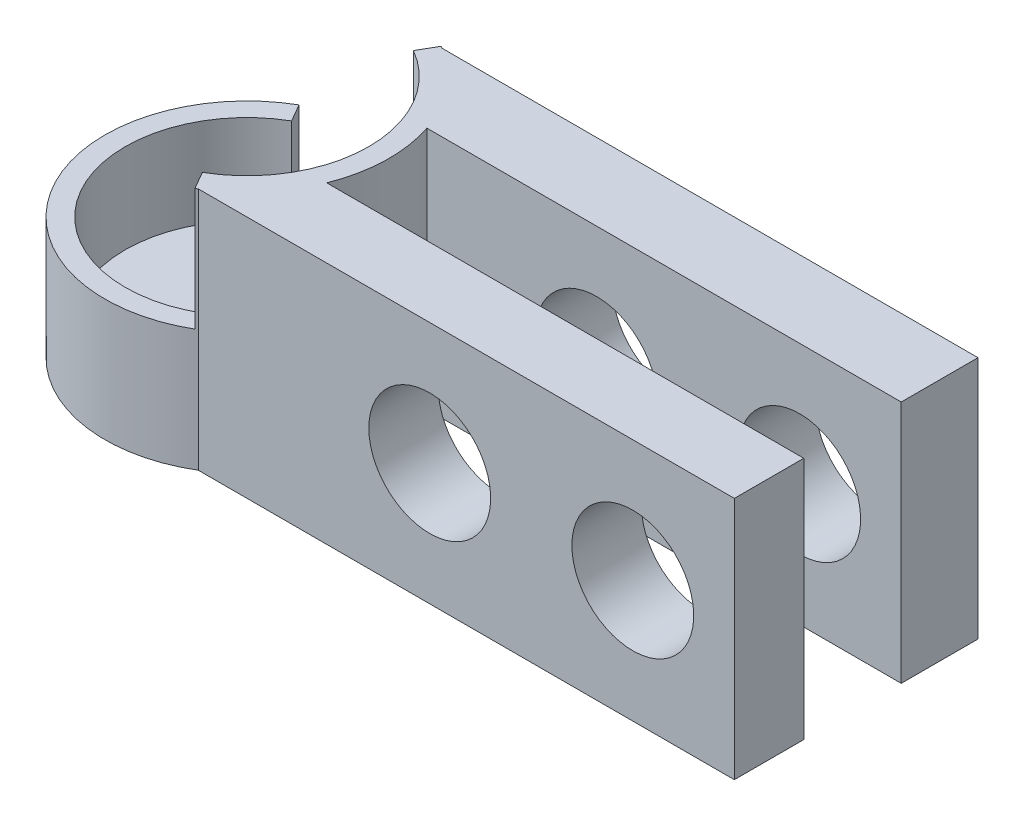
SolidWorks part; units mm, degrees
ref_plane "Front Plane" through (0, 0, 0) normal (0, 0, 1) x (1, 0, 0)
ref_plane "Top Plane" through (0, 0, 0) normal (0, 1, 0) x (1, 0, 0)
ref_plane "Right Plane" through (0, 0, 0) normal (1, 0, 0) x (0, 0, -1)
sketch "Sketch1" plane through (0, 0, 0) normal (0, 1, 0) x (1, 0, 0)
  line L2 (9.0139, 15) -> (75, 15)
  line L4 (9.0139, -15) -> (75, -15)
  line L5 (75, 15) -> (75, 5.5491)
  line L6 (75, -6.4509) -> (75, -15)
  line L7 (75, 5.5491) -> (16.5969, 5.5491)
  line L9 (75, -6.4509) -> (16.2676, -6.4509)
  arc A0 (16.2676, -6.4509) -> (16.5969, 5.5491) centre (0, 0) ccw
  arc A1 (9.0139, 15) -> (9.0139, -15) centre (0, 0) ccw
  dimension "D1" = 35
extrude "Boss-Extrude1" add sketch "Sketch1" along normal blind 30
sketch "Sketch2" plane through (0, 0, 0) normal (0, 1, 0) x (1, 0, 0)
  line L1 (8.75, 15.1554) -> (7.5, 12.9904)
  line L2 (-8.75, 15.1554) -> (-7.5, 12.9904)
  circle A0 centre (0, 0) radius 17.5
  arc A1 (-7.5, 12.9904) -> (7.5, 12.9904) centre (0, 0) ccw
  arc A2 (0, 17.5) -> (8.75, 15.1554) centre (0, 0) cw
  arc A3 (0, 17.5) -> (-8.75, 15.1554) centre (0, 0) ccw
extrude "Cut-Extrude1" cut sketch "Sketch2" along normal blind 30 from offset 4 contours A1 L1 A2 A3 L2
sketch "Sketch3" plane through (0, 0, 0) normal (0, 1, 0) x (1, 0, 0)
  line L0 (0, 0) -> (6.7175, 6.7175)
  circle A0 centre (6.7175, 6.7175) radius 2
  circle A1 centre (6.7175, -6.7175) radius 2
  circle A2 centre (-6.7175, -6.7175) radius 2
  circle A3 centre (-6.7175, 6.7175) radius 2
  point P13 (0, 0)
  dimension "D2" = 4
  dimension "D1" = 9.5
extrude "Cut-Extrude2" cut sketch "Sketch3" along normal blind 9.5 contours A2 | A3 | A1 | A0
sketch "Sketch4" plane through (0, 0, 0) normal (0, 1, 0) x (1, 0, 0)
  line L0 (0, 0) -> (8.75, -15.1554)
  line L1 (0, 0) -> (8.75, 15.1554)
  circle A0 centre (0, 0) radius 17.5
extrude "Cut-Extrude3" cut sketch "Sketch4" along normal blind 20 from offset 15 contours L1 A0 L0
sketch "Sketch5" plane through (0, 0, 0) normal (0, 0, 1) x (1, 0, 0)
  line L0 (75, 15) -> (62.5, 15) construction
  line L1 (75, 30) -> (75, 0) construction
  line L2 (62.5, 15) -> (37.5, 15) construction
  circle A0 centre (62.5, 15) radius 7.5
  circle A1 centre (37.5, 15) radius 7.5
  dimension "D1" = 12.5
  dimension "D2" = 25
extrude "Cut-Extrude4" cut sketch "Sketch5" against normal blind 20 and the other way blind 20
